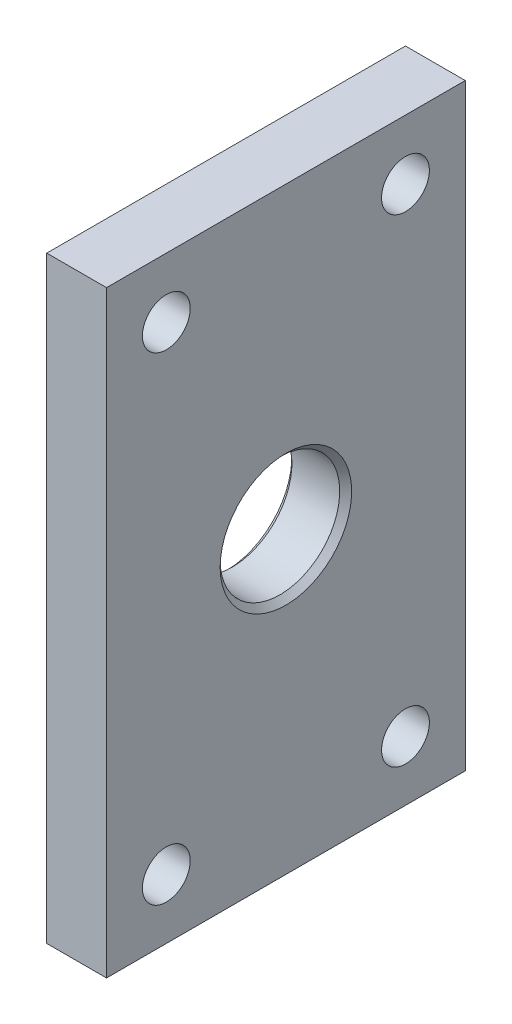
SolidWorks part; units mm, degrees
ref_plane "Front Plane" through (0, 0, 0) normal (1, 0, 0) x (0, 1, 0)
ref_plane "Top Plane" through (0, 0, 0) normal (0, 0, 1) x (0, 1, 0)
ref_plane "Right Plane" through (0, 0, 0) normal (0, 1, 0) x (-1, 0, 0)
sketch "Sketch1" plane through (0, 0, 0) normal (1, 0, 0) x (0, 1, 0)
  line L1 (0, 0) -> (100, 0)
  line L2 (0, 0) -> (0, 60)
  line L3 (0, 60) -> (100, 60)
  line L4 (100, 0) -> (100, 60)
extrude "Boss-Extrude1" add sketch "Sketch1" along normal blind 10
sketch "Sketch2" plane through (0, 0, 0) normal (1, 0, 0) x (0, 1, 0)
  circle A0 centre (10, 10) radius 4
extrude "Cut-Extrude2" cut sketch "Sketch2" against normal through all from offset 10
sketch "Sketch3" plane through (0, 0, 0) normal (1, 0, 0) x (0, 1, 0)
  circle A0 centre (90, 10) radius 4
  circle A1 centre (10, 50) radius 4
  circle A2 centre (90, 50) radius 4
extrude "Cut-Extrude4" cut sketch "Sketch3" against normal through all from offset 10
sketch "Sketch4" plane through (0, 0, 0) normal (1, 0, 0) x (0, 1, 0)
  circle A0 centre (50, 30) radius 10
extrude "Cut-Extrude6" cut sketch "Sketch4" against normal through all from offset 10
chamfer "Chamfer1" distance 1 angle 45 2 edges at (0, 50, 20) (10, 50, 20)
